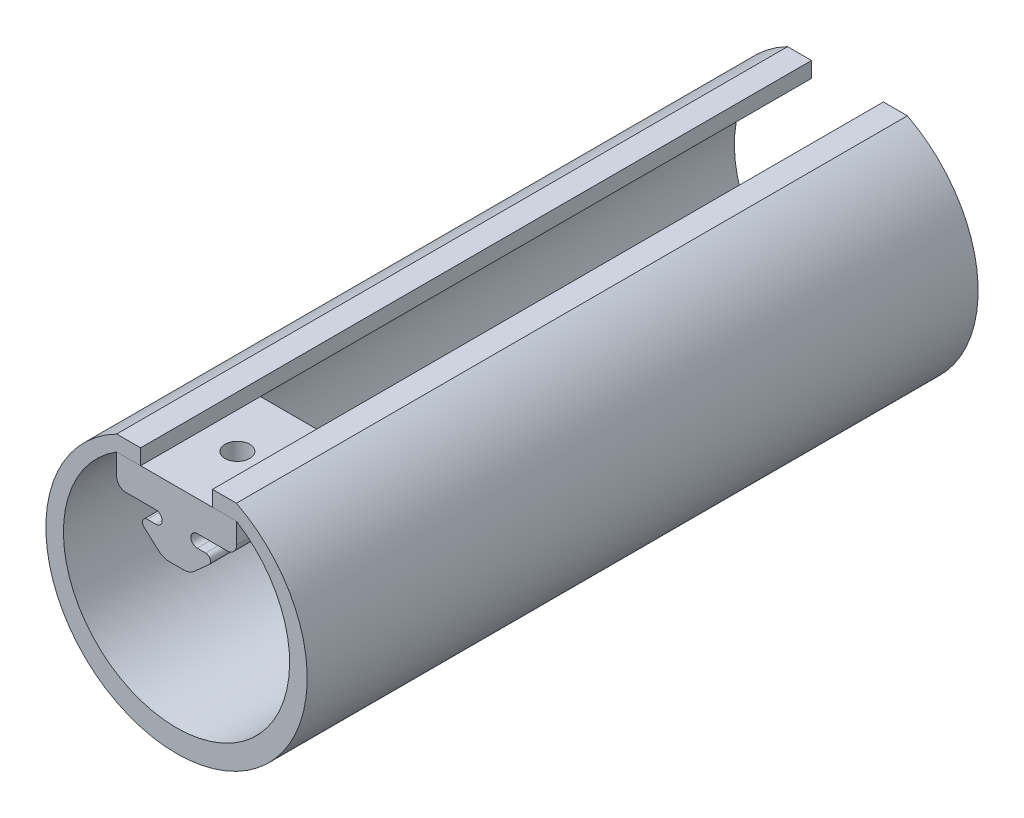
SolidWorks part; units mm, degrees
material "6105-T5 Aluminum"
ref_plane "Front Plane" through (0, 0, 0) normal (0, 0, 1) x (1, 0, 0)
ref_plane "Top Plane" through (0, 0, 0) normal (0, 1, 0) x (1, 0, 0)
ref_plane "Right Plane" through (0, 0, 0) normal (1, 0, 0) x (0, 0, -1)
sketch "Sketch1" plane through (0, 0, 0) normal (0, 0, 1) x (1, 0, 0)
  line L14 (4.315, 12.745) -> (10.5321, 12.745)
  line L15 (12.505, 14.7079) -> (12.505, 19.095)
  line L16 (6.085, 10.115) -> (4.315, 10.115)
  line L17 (3.6646, 5.583) -> (6.7586, 8.3524)
  line L28 (1.5504, 4.775) -> (-1.5504, 4.775)
  line L29 (-3.6646, 5.583) -> (-6.7586, 8.3524)
  line L30 (-6.085, 10.115) -> (-4.315, 10.115)
  line L31 (-12.495, 14.7079) -> (-12.495, 19.095)
  line L32 (-4.315, 12.745) -> (-10.5321, 12.745)
  line L36 (-15.7643, 0) -> (12.505, 0) construction
  line L37 (0, 13.9334) -> (0, -12.3541) construction
  line L38 (-12.495, 19.095) -> (12.505, 19.095)
  arc A12 (4.315, 10.115) -> (4.315, 12.745) centre (4.315, 11.43) cw
  arc A13 (6.085, 10.115) -> (6.7586, 8.3524) centre (6.085, 9.105) cw
  arc A14 (3.6646, 5.583) -> (1.5504, 4.775) centre (1.5504, 7.945) cw
  arc A24 (-3.6646, 5.583) -> (-1.5504, 4.775) centre (-1.5504, 7.945) ccw
  arc A25 (-6.085, 10.115) -> (-6.7586, 8.3524) centre (-6.085, 9.105) ccw
  arc A26 (-4.315, 10.115) -> (-4.315, 12.745) centre (-4.315, 11.43) ccw
  arc A29 (10.5321, 12.745) -> (12.505, 14.7079) centre (10.5421, 14.7079) ccw
  arc A30 (-10.5321, 12.745) -> (-12.495, 14.7079) centre (-10.5321, 14.7079) cw
  dimension "D4" = 14.19
  dimension "D5" = 5.34
  dimension "D6" = 6
  dimension "D7" = 1.01
  dimension "D8" = 6.35
  dimension "D3" = 3.17
  dimension "D2" = 25
  dimension "D10" = 2.63
extrude "Extrude1" add sketch "Sketch1" against normal blind 25
sketch "Sketch2" plane through (0, 19.095, 0) normal (0, 1, 0) x (1, 0, 0)
  line L0 (0, 50.8) -> (0, 0) construction
  line L3 (-12.495, 25) -> (-12.495, 0) construction
  line L4 (-12.495, 12.5) -> (12.5, 12.5) construction
  circle A1 centre (0, 12.7) radius 2.5797
extrude "Cut-Extrude1" cut sketch "Sketch2" against normal through all
sketch "Sketch5" plane through (0, 0, 0) normal (0, 0, 1) x (1, 0, 0)
  line L0 (-12.495, 19.095) -> (-12.495, 22.3324)
  line L1 (-12.495, 22.3324) -> (-7.495, 22.3324)
  line L2 (12.505, 22.3324) -> (12.505, 19.095)
  line L3 (-7.495, 22.3324) -> (-7.495, 19.095)
  line L4 (12.505, 19.095) -> (-12.495, 19.095) construction
  line L5 (7.505, 22.3324) -> (7.505, 19.095)
  line L6 (-12.495, 22.3324) -> (-7.495, 22.3324)
  line L7 (-7.495, 19.095) -> (-12.495, 19.095)
  line L8 (7.505, 22.3324) -> (12.505, 22.3324)
  line L9 (12.505, 19.095) -> (7.505, 19.095)
  line L10 (7.505, 22.3324) -> (12.505, 22.3324)
  arc A0 (-12.495, 19.095) -> (12.505, 19.095) centre (0.005, -0.9197) ccw
  arc A1 (-12.495, 22.3324) -> (12.505, 22.3324) centre (0.005, -1.9007) ccw
  line M3 (12.505, 19.095) -> (-12.495, 19.095)
  dimension "D1" = 5
  dimension "D2" = 5
extrude "Boss-Extrude1" add sketch "Sketch5" against normal blind 140 separate body contours L0 A1 L2 A0 | L3 L1 L0 M3 | L8 L5 L2 M3
